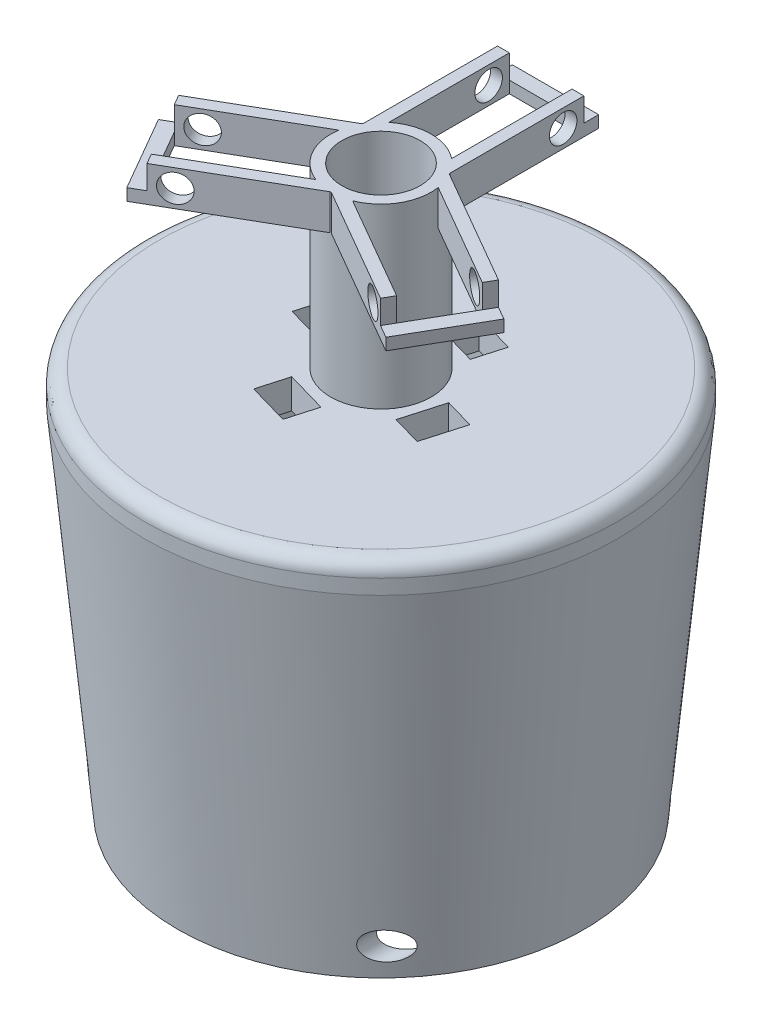
SolidWorks part; units mm, degrees
ref_plane "Front Plane" through (0, 0, 0) normal (0, 0, 1) x (1, 0, 0)
ref_plane "Top Plane" through (0, 0, 0) normal (0, 1, 0) x (1, 0, 0)
ref_plane "Right Plane" through (0, 0, 0) normal (1, 0, 0) x (0, 0, -1)
sketch "Sketch2" plane through (0, 0, 0) normal (0, 1, 0) x (1, 0, 0)
  circle A0 centre (0, 0) radius 32.5
  circle A1 centre (0, 0) radius 30
  dimension "D1" = 65
  dimension "D2" = 60
ref_plane "Plane4" through (0, 80, 0) normal (0, 1, 0) x (1, 0, 0)
sketch "Sketch3" plane through (0, 80, 0) normal (0, 1, 0) x (1, 0, 0)
  circle A0 centre (0, 0) radius 40
  circle A1 centre (0, 0) radius 37.5
  dimension "D1" = 80
  dimension "D2" = 75
loft "Loft5" add section "Sketch3" section "Sketch2"
sketch "Sketch21" plane through (0, 80, 0) normal (0, 1, 0) x (1, 0, 0)
  circle A0 centre (0, 0) radius 37.5 construction
  circle A1 centre (0, 0) radius 37.5
sketch "Sketch22" plane through (0, 0, 0) normal (0, -1, 0) x (1, 0, 0)
  circle A0 centre (0, 0) radius 30 construction
  circle A1 centre (0, 0) radius 30
loft "Cut-Loft10" cut profiles "Sketch22", "Sketch21"
sketch "Sketch24" plane through (0, 0, 0) normal (0, -1, 0) x (1, 0, 0)
  circle A0 centre (0, 0) radius 40
  dimension "D1" = 80
extrude "Cut-Extrude2" cut sketch "Sketch24" against normal blind 20
sketch "Sketch25" plane through (0, 80, 0) normal (0, 1, 0) x (1, 0, 0)
  circle A0 centre (0, 0) radius 40
  dimension "D1" = 80
extrude "Boss-Extrude2" add sketch "Sketch25" along normal blind 5
sketch "IMPORTANT ONE" plane through (0, 85, 0) normal (0, 1, 0) x (1, 0, 0)
  line L1 (-0.85, 5.8166) -> (-0.85, 5.7879)
  line L8 (0.85, 5.8166) -> (0.85, 5.7879)
  line L9 (-0.6506, 10.8004) -> (6.271, 8.8174)
  line L10 (-0.6506, 10.8004) -> (0.7816, 15.7993)
  line L11 (6.271, 8.8174) -> (7.7032, 13.8163)
  line L12 (0.7816, 15.7993) -> (7.7032, 13.8163)
  circle A5 centre (0, 0) radius 6.62
  circle A6 centre (0, 0) radius 13.3
  point P3 (6.9871, 11.3168)
  point P11 (0.0655, 13.2998)
  dimension "D2" = 13.24
  dimension "D5" = 26.6
  dimension "D6" = 7.2
  dimension "D7" = 5.2
extrude "Cut-Extrude3" cut sketch "IMPORTANT ONE" against normal blind 5
pattern_circular "CirPattern1" count 4 over 360 about axis through (0, 0, 0) along (0, 1, 0) of "Cut-Extrude3"
sketch "Sketch32" plane through (0, 0, 0) normal (0, 0, 1) x (1, 0, 0)
  line L0 (-34.375, 20) -> (34.375, 20)
  line L1 (0, 20) -> (0, 25)
  line L2 (0, 25) -> (-25, 25)
  line L3 (0, 25) -> (25, 25)
  circle A0 centre (-25, 25) radius 2.5
  circle A1 centre (25, 25) radius 2.5
  dimension "D4" = 5
  dimension "D5" = 5
  dimension "D1" = 5
  dimension "D2" = 25
  dimension "D3" = 25
extrude "Cut-Extrude6" cut sketch "Sketch32" against normal through all and the other way through all contours A0 | A1
fillet "Fillet1" radius 2.5 1 edges at (0, 85, 40)
sketch "Sketch33" plane through (0, 85, 0) normal (0, 1, 0) x (1, 0, 0)
  circle A0 centre (0, 0) radius 6.62
  circle A1 centre (0, 0) radius 8.5
  dimension "D1" = 13.24
  dimension "D2" = 17
extrude "Boss-Extrude3" add sketch "Sketch33" along normal blind 30
sketch "Sketch34" plane through (0, 115, 0) normal (0, 1, 0) x (1, 0, 0)
  line L0 (0, 0) -> (0, 27) construction
  line L1 (0, 27) -> (1.25, 27) construction
  line L2 (0, 8.5) -> (5.3, 8.5)
  line L3 (0, 8.5) -> (0, 27)
  line L4 (0, 27) -> (5.3, 27)
  line L5 (5.3, 8.5) -> (5.3, 27)
  line L6 (5.3, 27) -> (7.3, 27)
  line L7 (5.3, 27) -> (5.3, 4.3543)
  line L8 (5.3, 4.3543) -> (7.3, 4.3543)
  line L9 (7.3, 27) -> (7.3, 4.3543)
  line L10 (1.25, 27) -> (1.25, 6.5009) construction
  line L11 (1.25, 27) -> (1.25, 23.5) construction
  circle A0 centre (0, 0) radius 6.5
  circle A1 centre (0, 0) radius 8.5
  circle A2 centre (0, 0) radius 6.62 construction
  circle M4 centre (0, 0) radius 8.5
  dimension "D1" = 13
  dimension "D2" = 17
  dimension "D3" = 27
  dimension "D4" = 5.3
  dimension "D5" = 2
  dimension "D6" = 1.25
  dimension "D7" = 3.5
  dimension "D8" = 16.9991
extrude "Boss-Extrude4" add sketch "Sketch34" against normal blind 6 contours L9 L6 L5 L7 M4
sketch "Sketch35" plane through (7.3, 0, 0) normal (1, 0, 0) x (0, 0, -1)
  line L0 (27, 115) -> (27, 112) construction
  line L1 (27, 109) -> (27, 115) construction
  line L2 (27, 112) -> (23.5, 112) construction
  circle A0 centre (23.5, 112) radius 2.33
  dimension "D3" = 4.66
  dimension "D1" = 3
  dimension "D2" = 3.5
extrude "Cut-Extrude7" cut sketch "Sketch35" against normal up to surface (2 mm away) up to face at (5.3, 112, -16.8226)
mirror "Mirror1" about plane through (0, 0, 0) normal (1, 0, 0) of "Cut-Extrude7", "Boss-Extrude4"
sketch "Sketch36" plane through (0, 0, -27) normal (0, 0, -1) x (-1, 0, 0)
  line L0 (7.3, 109) -> (7.3, 115) construction
  line L1 (-7.3, 109) -> (7.3, 109)
  line L2 (-7.3, 109) -> (-7.3, 111)
  line L3 (-7.3, 111) -> (7.3, 111)
  line L4 (7.3, 109) -> (7.3, 111)
  dimension "D1" = 2
extrude "Boss-Extrude5" add sketch "Sketch36" along normal blind 2.5
pattern_circular "CirPattern2" count 3 over 360 about axis through (0, 0, 0) along (0, 1, 0) of "Mirror1", "Boss-Extrude5", "Boss-Extrude4", "Cut-Extrude7"
scale "Scale1" scale about centroid uniform scaling yes scale factor 0.8
